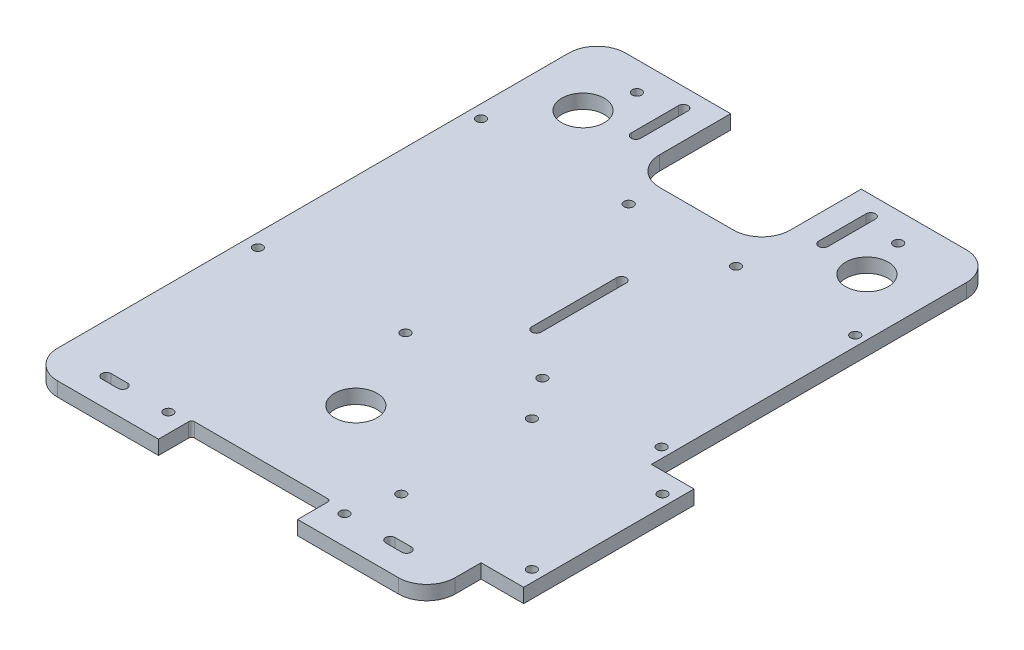
SolidWorks part; units mm, degrees
ref_plane "前视基准面" through (0, 0, 0) normal (0, 0, 1) x (1, 0, 0)
ref_plane "上视基准面" through (0, 0, 0) normal (0, 1, 0) x (1, 0, 0)
ref_plane "右视基准面" through (0, 0, 0) normal (1, 0, 0) x (0, 0, -1)
sketch "草图1" plane through (0, 0, 0) normal (0, 1, 0) x (1, 0, 0)
  line L0 (120, 0) -> (125, 0)
  line L1 (10, 0) -> (120, 0)
  line L5 (96.35, -23.35) -> (96.35, -6.65)
  line L7 (30.35, -6.65) -> (30.35, -23.35)
  line L9 (33.65, -23.35) -> (33.65, -6.65)
  line L11 (99.65, -6.65) -> (99.65, -23.35)
  line L40 (88.5, -188.35) -> (41.5, -188.35)
  line L44 (17.85, -188.35) -> (12.15, -188.35)
  line L52 (112.15, -188.35) -> (117.85, -188.35)
  line L53 (10, 0) -> (5, 0)
  line L58 (135, -120.9) -> (150, -120.9)
  line L59 (150, -120.9) -> (150, -180.9)
  line L60 (135, -10) -> (135, -120.9)
  line L61 (135, -180.9) -> (150, -180.9)
  line L62 (135, -180.9) -> (135, -190)
  line L68 (-5, -10) -> (-5, -190)
  line L70 (40.5, -189.35) -> (40.5, -200)
  line L71 (40.5, -200) -> (5, -200)
  line L72 (89.5, -189.35) -> (89.5, -200)
  line L73 (89.5, -200) -> (125, -200)
  line L74 (12.15, -191.65) -> (17.85, -191.65)
  line L75 (112.15, -191.65) -> (117.85, -191.65)
  circle A4 centre (19, -10) radius 1.65
  circle A5 centre (111, -10) radius 1.65
  circle A6 centre (15, -25) radius 7.5
  circle A7 centre (115, -25) radius 7.5
  circle A8 centre (-0.4, -45.5) radius 1.65
  circle A9 centre (51.6, -45.5) radius 1.65
  circle A10 centre (51.6, -124.1) radius 1.65
  circle A11 centre (-0.4, -124.1) radius 1.65
  circle A12 centre (89.5, -45.6) radius 1.65
  circle A13 centre (131.5, -45.6) radius 1.65
  circle A14 centre (131.5, -113.8) radius 1.65
  circle A15 centre (89.5, -113.8) radius 1.65
  circle A16 centre (146, -128) radius 1.65
  circle A17 centre (100, -128) radius 1.65
  circle A18 centre (100, -174) radius 1.65
  circle A19 centre (146, -174) radius 1.65
  circle A20 centre (65, -155) radius 7.5
  circle A21 centre (96, -190) radius 1.65
  circle A22 centre (34, -190) radius 1.65
  arc A23 (30.35, -6.65) -> (33.65, -6.65) centre (32, -6.65) cw
  arc A24 (30.35, -23.35) -> (33.65, -23.35) centre (32, -23.35) ccw
  arc A25 (99.65, -23.35) -> (96.35, -23.35) centre (98, -23.35) cw
  arc A26 (96.35, -6.65) -> (99.65, -6.65) centre (98, -6.65) cw
  arc A29 (125, 0) -> (135, -10) centre (125, -10) cw
  arc A30 (5, 0) -> (-5, -10) centre (5, -10) ccw
  arc A31 (135, -190) -> (125, -200) centre (125, -190) cw
  arc A32 (-5, -190) -> (5, -200) centre (5, -190) ccw
  arc A33 (89.5, -189.35) -> (88.5, -188.35) centre (88.5, -189.35) ccw
  arc A34 (41.5, -188.35) -> (40.5, -189.35) centre (41.5, -189.35) ccw
  arc A35 (17.85, -188.35) -> (19.5, -190) centre (17.85, -190) cw
  arc A36 (12.15, -188.35) -> (10.5, -190) centre (12.15, -190) ccw
  arc A37 (110.5, -190) -> (112.15, -188.35) centre (112.15, -190) cw
  arc A38 (119.5, -190) -> (117.85, -188.35) centre (117.85, -190) ccw
  arc A39 (10.5, -190) -> (12.15, -191.65) centre (12.15, -190) ccw
  arc A40 (19.5, -190) -> (17.85, -191.65) centre (17.85, -190) cw
  arc A41 (110.5, -190) -> (112.15, -191.65) centre (112.15, -190) ccw
  arc A42 (117.85, -191.65) -> (119.5, -190) centre (117.85, -190) ccw
  point P13 (0, 0)
  point P39 (89.5, -188.35)
  point P79 (40.5, -188.35)
  point P88 (135, 0)
  point P91 (-5, 0)
  point P94 (10.5, -188.35)
  point P97 (110.5, -188.35)
  point P100 (119.5, -188.35)
  dimension "D4" = 92
  dimension "D10" = 10
  dimension "D12" = 20.6
  dimension "D14" = 42
  dimension "D16" = 15
  dimension "D17" = 25
  dimension "D21" = 3.3
  dimension "D26" = 3.3
  dimension "D31" = 3.3
  dimension "D32" = 3.3
  dimension "D33" = 3.3
  dimension "D34" = 15
  dimension "D6" = 1.65
  dimension "D50" = 25
  dimension "D35" = 4.6
  dimension "D53" = 15
  dimension "D11" = 52
  dimension "D15" = 14.2
  dimension "D18" = 46
  dimension "D23" = 7.1
  dimension "D13" = 46
  dimension "D28" = 4
  dimension "D36" = 1
  dimension "D38" = 1.65
  dimension "D7" = 16.7
  dimension "D9" = 6.65
  dimension "D19" = 52
  dimension "D20" = 78.6
  dimension "D22" = 45.5
  dimension "D24" = 42
  dimension "D25" = 68.2
  dimension "D27" = 60
  dimension "D29" = 46
  dimension "D30" = 46
  dimension "D39" = 49
  dimension "D41" = 62
  dimension "D42" = 15
  dimension "D43" = 16.7
  dimension "D44" = 3.3
  dimension "D54" = 15
extrude "凸台-拉伸1" add sketch "草图1" along normal blind 5
sketch "草图2" plane through (0, 0, 0) normal (0, -1, 0) x (1, 0, 0)
  line L0 (33.65, 23.35) -> (33.65, 6.65) construction
  line L1 (125, 0) -> (5, 0) construction
  line L2 (96.35, 6.65) -> (96.35, 23.35) construction
  line L3 (42, 0) -> (88, 0)
  line L4 (42, 0) -> (42, 25)
  line L5 (52, 35) -> (78, 35)
  line L6 (88, 0) -> (88, 25)
  arc A0 (78, 35) -> (88, 25) centre (78, 25) cw
  arc A1 (42, 25) -> (52, 35) centre (52, 25) cw
  point P12 (88, 35)
  dimension "D4" = 10
  dimension "D1" = 8.35
  dimension "D2" = 8.35
  dimension "D3" = 35
extrude "切除-拉伸1" cut sketch "草图2" against normal up to surface (5 mm away) up to face at (65, 5, 162.5)
sketch "草图4" plane through (0, 0, 0) normal (0, 1, 0) x (1, 0, 0)
  line L0 (73.6, -70) -> (73.6, -100) construction
  line L1 (75.25, -70) -> (75.25, -100)
  line L2 (71.95, -70) -> (71.95, -100)
  line L3 (42, -25) -> (42, 0) construction
  line L4 (78, -35) -> (52, -35) construction
  arc A0 (75.25, -70) -> (71.95, -70) centre (73.6, -70) ccw
  arc A1 (71.95, -100) -> (75.25, -100) centre (73.6, -100) ccw
  point P2 (73.6, -85)
  dimension "D1" = 31.6
  dimension "D2" = 3.3
  dimension "D3" = 30
  dimension "D4" = 50
extrude "切除-拉伸3" cut sketch "草图4" along normal up to surface (5 mm away) up to face at (65, 5, 162.5)
